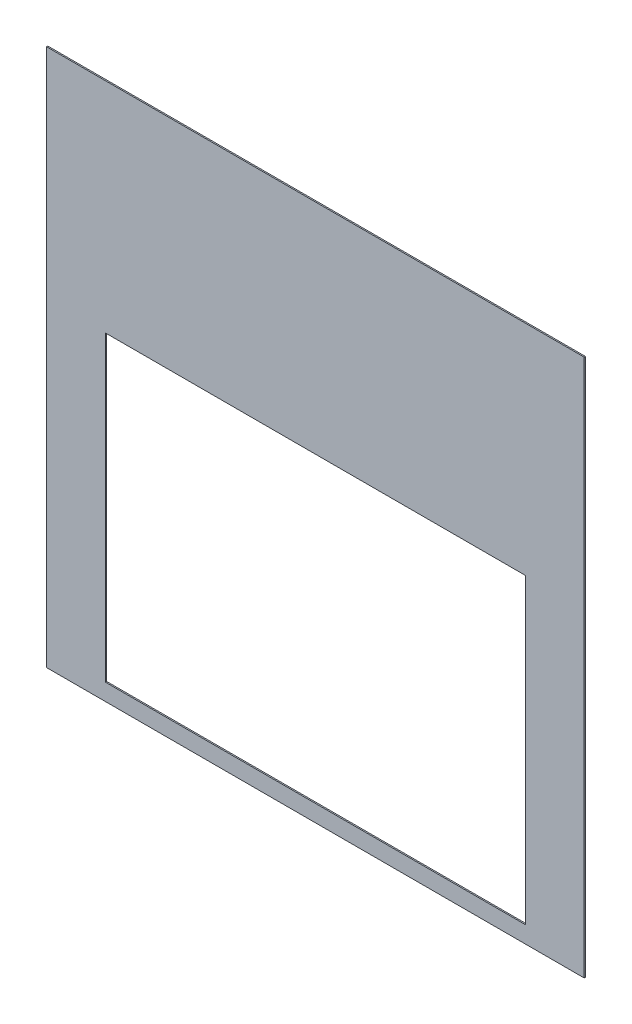
SolidWorks part; units mm, degrees
ref_plane "Front Plane" through (0, 0, 0) normal (0, 0, 1) x (1, 0, 0)
ref_plane "Top Plane" through (0, 0, 0) normal (0, 1, 0) x (1, 0, 0)
ref_plane "Right Plane" through (0, 0, 0) normal (1, 0, 0) x (0, 0, -1)
other "Configuration Table"
sketch "Sketch1" plane through (0, 0, 0) normal (0, 0, 1) x (1, 0, 0)
  line L1 (30, 700) -> (670, 700)
  line L2 (30, 700) -> (30, 1340)
  line L3 (30, 1340) -> (670, 1340)
  line L4 (670, 700) -> (670, 1340)
extrude "PRESS_panel_pres_agzi_1" add sketch "Sketch1" along normal blind 1.5 from offset 38.5 separate body
sketch "Sketch2" plane through (0, 0, 0) normal (0, 0, 1) x (1, 0, 0)
  line L1 (100, 720) -> (600, 720)
  line L2 (100, 720) -> (100, 1080)
  line L3 (100, 1080) -> (600, 1080)
  line L4 (600, 720) -> (600, 1080)
extrude "PRESS_panel_pres_agzi_2" cut sketch "Sketch2" along normal blind 3.5 from offset 37.5
